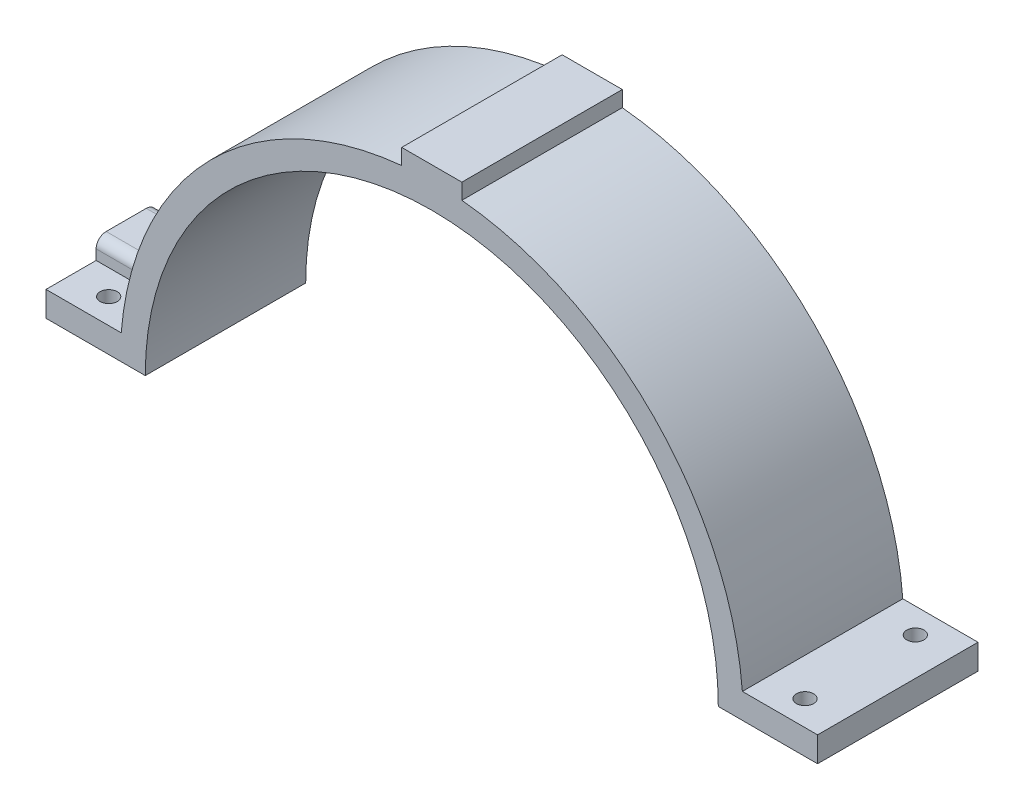
SolidWorks part; units mm, degrees
material "ABS"
ref_plane "正面" through (0, 0, 0) normal (0, 0, 1) x (1, 0, 0)
ref_plane "平面" through (0, 0, 0) normal (0, 1, 0) x (1, 0, 0)
ref_plane "右側面" through (0, 0, 0) normal (1, 0, 0) x (0, 0, -1)
sketch "ｽｹｯﾁ1" plane through (0, 0, 0) normal (0, 0, 1) x (1, 0, 0)
  line L0 (-57.15, 0) -> (-62.15, 0)
  line L1 (57.15, 0) -> (62.15, 0)
  arc A2 (-62.15, 0) -> (62.15, 0) centre (0, 0) cw
  arc A3 (-57.15, 0) -> (57.15, 0) centre (0, 0) cw
  dimension "D1" = 114.3
  dimension "D2" = 5
extrude "ﾎﾞｽ - 押し出し1" add sketch "ｽｹｯﾁ1" along normal blind 32
sketch "ｽｹｯﾁ2" plane through (0, 0, 32) normal (0, 0, 1) x (1, 0, 0)
  line L0 (0, 0) -> (0, 147.9043) construction
  line L1 (6, 61.8597) -> (6, 65)
  line L2 (6, 65) -> (-6, 65)
  line L3 (-6, 65) -> (-6, 61.8597)
  line L4 (-6, 61.8597) -> (6, 61.8597)
  line L5 (61.9485, 5) -> (61.9485, 0)
  line L6 (57.15, 0) -> (62.15, 0) construction
  line L7 (61.9485, 0) -> (76.9485, 0)
  line L8 (76.9485, 0) -> (76.9485, 5)
  line L9 (76.9485, 5) -> (61.9485, 5)
  line L10 (-76.9485, 0) -> (-76.9485, 5)
  line L11 (-61.9485, 0) -> (-76.9485, 0)
  line L12 (-61.9485, 5) -> (-61.9485, 0)
  line L13 (-76.9485, 5) -> (-61.9485, 5)
  arc A1 (62.15, 0) -> (-62.15, 0) centre (0, 0) ccw construction
  dimension "D2" = 65
  dimension "D1" = 6
  dimension "D3" = 15
  dimension "D4" = 5
extrude "ﾎﾞｽ - 押し出し2" add sketch "ｽｹｯﾁ2" against normal up to surface (32 mm away) up to face at (0, 29.825, 0)
sketch "ｽｹｯﾁ3" plane through (-76.9485, 0, 0) normal (-1, 0, 0) x (0, 0, 1)
  line L0 (0, 0) -> (32, 0) construction
  line L1 (10, 0) -> (22, 0)
  line L2 (10, 0) -> (10, 9)
  line L3 (10, 9) -> (22, 9)
  line L4 (22, 0) -> (22, 9)
  point P6 (16, 0)
  dimension "D1" = 12
  dimension "D2" = 9
extrude "ﾎﾞｽ - 押し出し3" add sketch "ｽｹｯﾁ3" against normal blind 19
sketch "ｽｹｯﾁ4" plane through (-76.9485, 0, 0) normal (-1, 0, 0) x (0, 0, 1)
  line L0 (0, 0) -> (32, 0) construction
  line L1 (10, 0) -> (22, 0)
  arc A0 (10, 0) -> (22, 0) centre (16, 0) cw
  dimension "D1" = 6
extrude "ｶｯﾄ - 押し出し1" cut sketch "ｽｹｯﾁ4" against normal blind 15
fillet "ﾌｨﾚｯﾄ1" radius 2 2 edges at (-69.2217, 9, 10) (-69.2217, 9, 22)
sketch "ｽｹｯﾁ5" plane through (0, 5, 0) normal (0, 1, 0) x (1, 0, 0)
  line L0 (-69.4485, 0) -> (-69.4485, -32) construction
  line L1 (-61.9485, 0) -> (-76.9485, 0) construction
  line L2 (-61.9485, -32) -> (-76.9485, -32) construction
  line L3 (76.9485, -16) -> (-76.9485, -16) construction
  line L4 (76.9485, 0) -> (76.9485, -32) construction
  line L5 (-76.9485, -20) -> (-76.9485, -12) construction
  line L6 (0, 0) -> (0, -32) construction
  line L7 (6, -32) -> (-6, -32) construction
  circle A0 centre (-69.4485, -5) radius 1.7114
  circle A1 centre (-69.4485, -27) radius 1.7114
  circle A2 centre (69.4485, -27) radius 1.7114
  circle A3 centre (69.4485, -5) radius 1.7114
  dimension "D1" = 3.4228
  dimension "D2" = 5
extrude "ｶｯﾄ - 押し出し2" cut sketch "ｽｹｯﾁ5" against normal up to next
